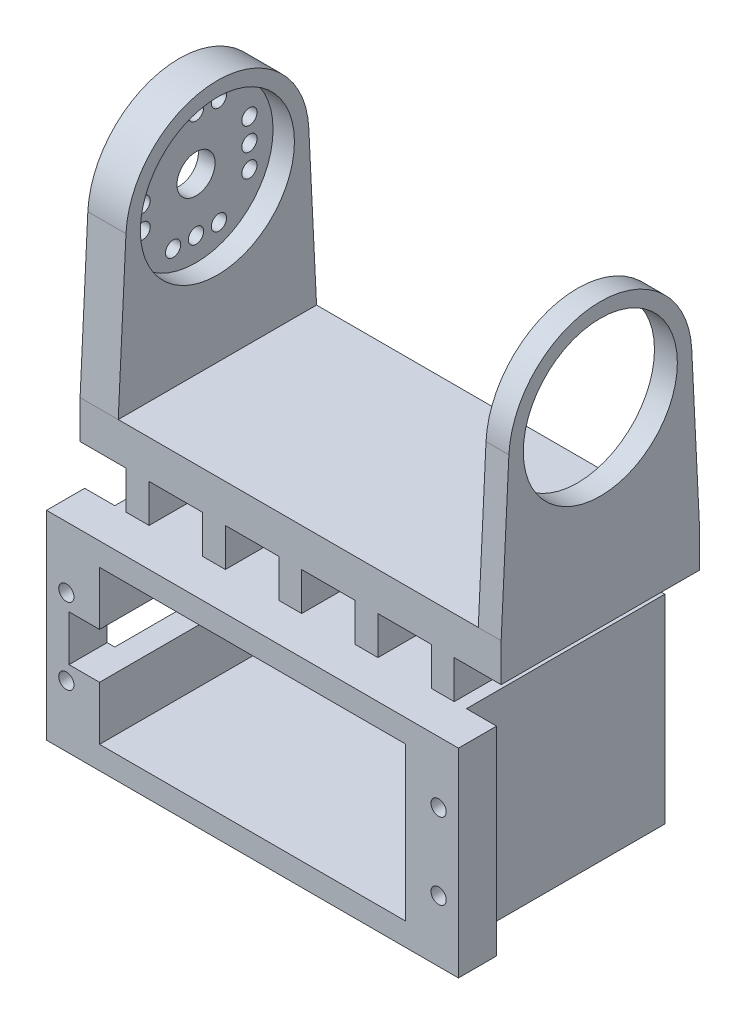
SolidWorks part; units mm, degrees
ref_plane "Front Plane" through (0, 0, 0) normal (0, 0, 1) x (1, 0, 0)
ref_plane "Top Plane" through (0, 0, 0) normal (0, 1, 0) x (1, 0, 0)
ref_plane "Right Plane" through (0, 0, 0) normal (1, 0, 0) x (0, 0, -1)
sketch "Sketch1" plane through (0, 0, 0) normal (0, 0, 1) x (1, 0, 0)
  line L0 (-23.05, 13.05) -> (23.05, 13.05)
  line L1 (-20.05, 10.05) -> (20.05, 10.05)
  line L2 (-20.05, 10.05) -> (-20.05, -10.05)
  line L3 (-20.05, -10.05) -> (20.05, -10.05)
  line L4 (20.05, 10.05) -> (20.05, -10.05)
  line L5 (-20.05, 10.05) -> (20.05, -10.05) construction
  line L6 (-20.05, -10.05) -> (20.05, 10.05) construction
  line L7 (23.05, 13.05) -> (23.05, -13.05)
  line L8 (-23.05, -13.05) -> (23.05, -13.05)
  line L9 (-23.05, 13.05) -> (-23.05, -13.05)
  point P0 (0, 0)
  dimension "D1" = 40.1
  dimension "D2" = 20.1
  dimension "D3" = 3
extrude "Boss-Extrude1" add sketch "Sketch1" along normal blind 28
sketch "Sketch2" plane through (0, 0, 0) normal (0, 0, -1) x (-1, 0, 0)
  line L1 (-23.05, 13.05) -> (23.05, 13.05)
  line L2 (-23.05, 13.05) -> (-23.05, -13.05)
  line L3 (-23.05, -13.05) -> (23.05, -13.05)
  line L4 (23.05, 13.05) -> (23.05, -13.05)
extrude "Boss-Extrude2" add sketch "Sketch2" along normal blind 3
sketch "Sketch3" plane through (0, 0, 28) normal (0, 0, 1) x (1, 0, 0)
  line L0 (0, 30.5481) -> (0, -21.7069) construction
  line L1 (-27, 13.05) -> (-23.05, 13.05)
  line L2 (-27, 13.05) -> (-27, -13.05)
  line L3 (-27, -13.05) -> (-23.05, -13.05)
  line L4 (-23.05, 13.05) -> (-23.05, -13.05)
  line L5 (-27, 13.05) -> (-23.05, -13.05) construction
  line L6 (-27, -13.05) -> (-23.05, 13.05) construction
  line L7 (27, -13.05) -> (23.05, 13.05) construction
  line L8 (27, 13.05) -> (23.05, -13.05) construction
  line L9 (23.05, 13.05) -> (23.05, -13.05)
  line L10 (27, -13.05) -> (23.05, -13.05)
  line L11 (27, 13.05) -> (27, -13.05)
  line L12 (27, 13.05) -> (23.05, 13.05)
  point P0 (-25.025, 0)
  dimension "D1" = 3.95
extrude "Boss-Extrude3" add sketch "Sketch3" against normal blind 5
sketch "Sketch4" plane through (0, 0, 28) normal (0, 0, 1) x (1, 0, 0)
  line L0 (27, -13.05) -> (27, 13.05) construction
  circle A0 centre (24.4, 5) radius 1
  circle A1 centre (24.4, -5) radius 1
  dimension "D5" = 2
  dimension "D1" = 2.6
  dimension "D2" = 2.6
  dimension "D3" = 10
  dimension "D4" = 5
extrude "Cut-Extrude1" cut sketch "Sketch4" against normal blind 13
mirror "Mirror1" about plane through (0, 0, 0) normal (1, 0, 0) of "Cut-Extrude1"
sketch "Sketch5" plane through (0, 0, -3) normal (0, 0, -1) x (-1, 0, 0)
  line L0 (23.05, -13.05) -> (23.05, 13.05) construction
  circle A0 centre (10.05, 0) radius 10
  dimension "D1" = 20
  dimension "D2" = 13
extrude "Boss-Extrude4" add sketch "Sketch5" along normal blind 2
sketch "Sketch7" plane through (0, 13.05, 0) normal (0, 1, 0) x (1, 0, 0)
  line L0 (-23.05, 3) -> (23.05, 3) construction
  line L1 (-21.55, 3) -> (-18.55, 3)
  line L2 (-21.55, 3) -> (-21.55, -23)
  line L3 (-21.55, -23) -> (-18.55, -23)
  line L4 (-18.55, 3) -> (-18.55, -23)
  line L5 (27, -28) -> (-27, -28) construction
  line L6 (-23.05, -23) -> (-23.05, 3) construction
  line L7 (-11.55, 3) -> (-11.55, -23)
  line L8 (-8.55, 3) -> (-8.55, -23)
  line L9 (-11.55, 3) -> (-8.55, 3)
  line L10 (-11.55, -23) -> (-8.55, -23)
  line L11 (-1.55, 3) -> (-1.55, -23)
  line L12 (1.45, 3) -> (1.45, -23)
  line L13 (-1.55, 3) -> (1.45, 3)
  line L14 (-1.55, -23) -> (1.45, -23)
  line L15 (8.45, 3) -> (8.45, -23)
  line L16 (11.45, 3) -> (11.45, -23)
  line L17 (8.45, 3) -> (11.45, 3)
  line L18 (8.45, -23) -> (11.45, -23)
  line L19 (18.45, 3) -> (18.45, -23)
  line L20 (21.45, 3) -> (21.45, -23)
  line L21 (18.45, 3) -> (21.45, 3)
  line L22 (18.45, -23) -> (21.45, -23)
  dimension "D1" = 0
  dimension "D2" = 5
  dimension "D3" = 3
  dimension "D4" = 1.5
  dimension "D5" = 5
extrude "Boss-Extrude5" add sketch "Sketch7" along normal blind 5
sketch "Sketch8" plane through (0, 18.05, 0) normal (0, 1, 0) x (1, 0, 0)
  line L1 (-27.6, 3) -> (27.6, 3)
  line L2 (-27.6, 3) -> (-27.6, -23)
  line L3 (-27.6, -23) -> (27.6, -23)
  line L4 (27.6, 3) -> (27.6, -23)
  dimension "D1" = 55.2
  dimension "D2" = 27.6
  dimension "D3" = 26
extrude "Boss-Extrude6" add sketch "Sketch8" along normal blind 5
sketch "Sketch9" plane through (-27.6, 0, 0) normal (-1, 0, 0) x (0, 0, 1)
  line L0 (-3, 23.05) -> (-1.9855, 43.6405)
  line L1 (23, 23.05) -> (21.9855, 43.6405)
  line L2 (-3, 23.05) -> (23, 23.05) construction
  line L3 (-3, 23.05) -> (23, 23.05)
  line L4 (-3, 23.05) -> (-3, 18.05) construction
  arc A0 (21.9855, 43.6405) -> (-1.9855, 43.6405) centre (10, 43.05) ccw
  point P10 (-3, 20.55)
  dimension "D1" = 24
  dimension "D2" = 20
  dimension "D3" = 13
extrude "Boss-Extrude7" add sketch "Sketch9" against normal blind 55.2
sketch "Sketch12" plane through (-27.6, 0, 0) normal (-1, 0, 0) x (0, 0, 1)
  line L0 (-3, 18.05) -> (-3, 13.05) construction
  circle A0 centre (10, 43.05) radius 2.5
  circle A1 centre (10, 50.05) radius 1
  circle A2 centre (13, 50.05) radius 1
  circle A3 centre (7, 50.05) radius 1
  circle A4 centre (17, 46.05) radius 1
  circle A5 centre (17, 43.05) radius 1
  circle A6 centre (17, 40.05) radius 1
  circle A7 centre (13, 36.05) radius 1
  circle A8 centre (10, 36.05) radius 1
  circle A9 centre (7, 36.05) radius 1
  circle A10 centre (3, 40.05) radius 1
  circle A11 centre (3, 43.05) radius 1
  circle A12 centre (3, 46.05) radius 1
  point P32 (10, 43.05)
  dimension "D1" = 13
  dimension "D3" = 2
  dimension "D2" = 20
  dimension "D4" = 3
  dimension "D5" = 3
  dimension "D6" = 0
  dimension "D7" = 7
  dimension "D8" = 4
extrude "Cut-Extrude2" cut sketch "Sketch12" against normal blind 13.2
sketch "Sketch13" plane through (27.6, 0, 0) normal (1, 0, 0) x (0, 0, -1)
  circle A0 centre (-10, 43.05) radius 10.1
  dimension "D1" = 20.2
extrude "Cut-Extrude3" cut sketch "Sketch13" against normal blind 13.2
sketch "Sketch14" plane through (0, 0, -3) normal (0, 0, -1) x (-1, 0, 0)
  line L0 (-27.6, 23.05) -> (27.6, 23.05) construction
  line L1 (-24.6, 23.05) -> (22.6, 23.05)
  line L2 (-24.6, 23.05) -> (-24.6, 55.05)
  line L3 (-24.6, 55.05) -> (22.6, 55.05)
  line L4 (22.6, 23.05) -> (22.6, 55.05)
  line L5 (27.6, 55.05) -> (-27.6, 55.05) construction
  line L6 (27.6, 43.6405) -> (27.6, 23.05) construction
  line L7 (-27.6, 55.05) -> (-27.6, 43.6405) construction
  dimension "D1" = 5
  dimension "D2" = 3
extrude "Cut-Extrude4" cut sketch "Sketch14" against normal blind 43.2
sketch "Sketch15" plane through (-22.6, 0, 0) normal (1, 0, 0) x (0, 0, -1)
  circle A0 centre (-10, 43.05) radius 10.1
extrude "Cut-Extrude5" cut sketch "Sketch15" against normal blind 2.8
sketch "Sketch16" plane through (0, 0, 28) normal (0, 0, 1) x (1, 0, 0)
  line L0 (-20.05, 10.05) -> (-20.05, -10.05) construction
  line L1 (-24.05, 3) -> (-20.05, 3)
  line L2 (-24.05, 3) -> (-24.05, -3)
  line L3 (-24.05, -3) -> (-20.05, -3)
  line L4 (-20.05, 3) -> (-20.05, -3)
  line L5 (-24.05, 3) -> (-20.05, -3) construction
  line L6 (-24.05, -3) -> (-20.05, 3) construction
  point P0 (-22.05, 0)
  dimension "D1" = 6
  dimension "D2" = 4
  dimension "D3" = 0
extrude "Cut-Extrude6" cut sketch "Sketch16" against normal blind 24
